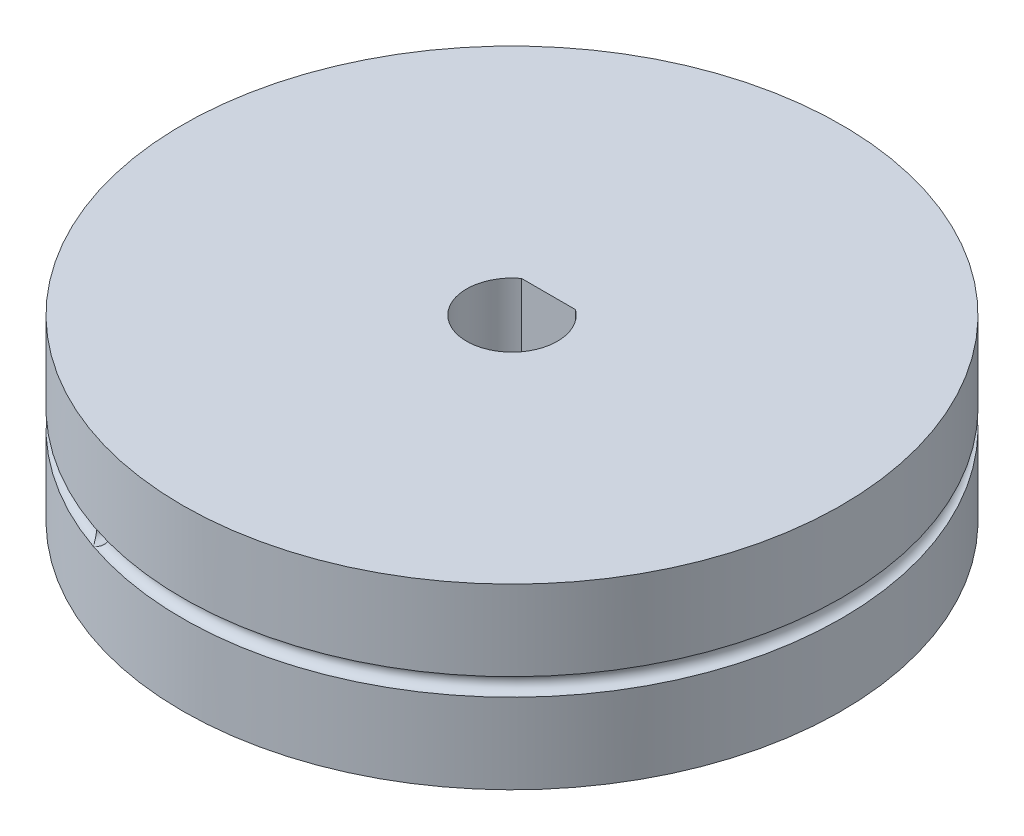
SolidWorks part; units mm, degrees
ref_plane "Front Plane" through (0, 0, 0) normal (0, 0, 1) x (1, 0, 0)
ref_plane "Top Plane" through (0, 0, 0) normal (0, 1, 0) x (1, 0, 0)
ref_plane "Right Plane" through (0, 0, 0) normal (1, 0, 0) x (0, 0, -1)
sketch "Sketch1" plane through (0, 0, 0) normal (0, 1, 0) x (1, 0, 0)
  circle A0 centre (0, 0) radius 18.5
  dimension "D1" = 37
extrude "Boss-Extrude1" add sketch "Sketch1" along normal blind 10
ref_axis "Axis1" through (0, 22.423, 0) along (0, -1, 0)
sketch "Sketch2" plane through (0, 0, 0) normal (0, 0, 1) x (1, 0, 0)
  line L1 (-18.5, 10) -> (-18.5, 0) construction
  circle A0 centre (-18.5, 5) radius 0.5
  point P2 (-18.5, 5)
  dimension "D1" = 1
revolve "Cut-Revolve1" cut sketch "Sketch2" angle 360 about axis through (0, 22.423, 0) along (0, -1, 0)
sketch "Sketch3" plane through (0, 10, 0) normal (0, 1, 0) x (1, 0, 0)
  line L0 (-1.5166, 2.05) -> (1.5166, 2.05)
  circle A0 centre (0, 0) radius 2.55
  point P5 (0, -2.55)
  dimension "D1" = 5.1
  dimension "D2" = 4.6
extrude "Cut-Extrude1" cut sketch "Sketch3" against normal up to next contours L0 A0
sketch "Sketch4" plane through (0, 0, 0) normal (0, 0, 1) x (1, 0, 0)
  line L0 (-18.5, 5.5) -> (-18.5, 4.5) construction
  line L1 (0, 22.423) -> (0, 0) construction
  circle A0 centre (-6, 5) radius 0.5
  point P6 (-18.5, 5)
  point P9 (0, 0)
  dimension "D1" = 1
  dimension "D2" = 6
extrude "Cut-Extrude2" cut sketch "Sketch4" against normal up to next and the other way up to next
